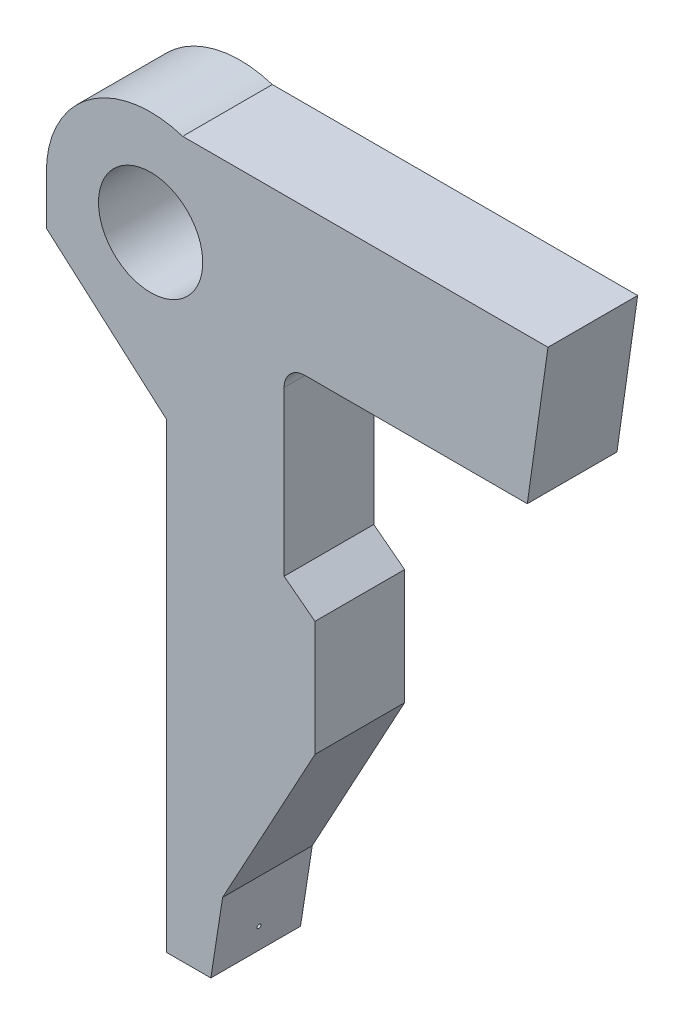
SolidWorks part; units mm, degrees
ref_plane "정면" through (0, 0, 0) normal (0, 0, 1) x (1, 0, 0)
ref_plane "윗면" through (0, 0, 0) normal (0, 1, 0) x (1, 0, 0)
ref_plane "우측면" through (0, 0, 0) normal (1, 0, 0) x (0, 0, -1)
sketch "스케치1" plane through (0, 0, 0) normal (0, 0, 1) x (1, 0, 0)
  line L0 (-5, 0) -> (-5, -2.3265)
  line L1 (0.7542, -29.5199) -> (2.8891, -29.5199)
  line L2 (6.4021, -11.0793) -> (6.4021, -3.2376)
  line L3 (7.4021, -2.2376) -> (18.0636, -2.2376)
  line L4 (18.0636, -2.2376) -> (19.056, 4.758)
  line L5 (2.8891, -29.5199) -> (3.4526, -25.8908)
  line L6 (-5, -2.3265) -> (0.7542, -7.3778)
  line L7 (0.7542, -7.3778) -> (0.7542, -29.5199)
  line L8 (19.056, 4.758) -> (1.5367, 4.758)
  line L9 (3.4526, -25.8908) -> (7.8804, -17.7409)
  line L10 (7.8804, -17.7409) -> (7.8804, -12.2111)
  line L11 (7.8804, -12.2111) -> (6.4021, -11.0793)
  circle A0 centre (0, 0) radius 2.5
  circle A1 centre (0, 0) radius 5
  arc A3 (6.4021, -3.2376) -> (7.4021, -2.2376) centre (7.4021, -3.2376) cw
  dimension "D1" = 5
  dimension "D2" = 10
  dimension "D3" = 1
extrude "보스-돌출1" add sketch "스케치1" along normal blind 4.3
sketch "스케치3" plane through (0.7542, 0, 0) normal (-1, 0, 0) x (0, 0, 1)
  line L0 (4.3, -29.5199) -> (0, -29.5199) construction
  circle A0 centre (2.1748, -27.02) radius 1.825
  point P2 (2.15, -29.5199)
  dimension "D2" = 3.65
  dimension "D1" = 2.5
extrude "컷-돌출1" cut sketch "스케치3" against normal blind 1.8
sketch "스케치4" plane through (2.5542, 0, 0) normal (-1, 0, 0) x (0, 0, 1)
  line L0 (2.1748, -25.195) -> (2.1748, -28.845) construction
  circle A0 centre (2.1748, -27.02) radius 1.825 construction
  circle A1 centre (2.1748, -27.02) radius 1.825 construction
  circle A2 centre (2.1748, -28.345) radius 0.1
  dimension "D1" = 0.5
extrude "컷-돌출2" cut sketch "스케치4" against normal up to next contours A2
